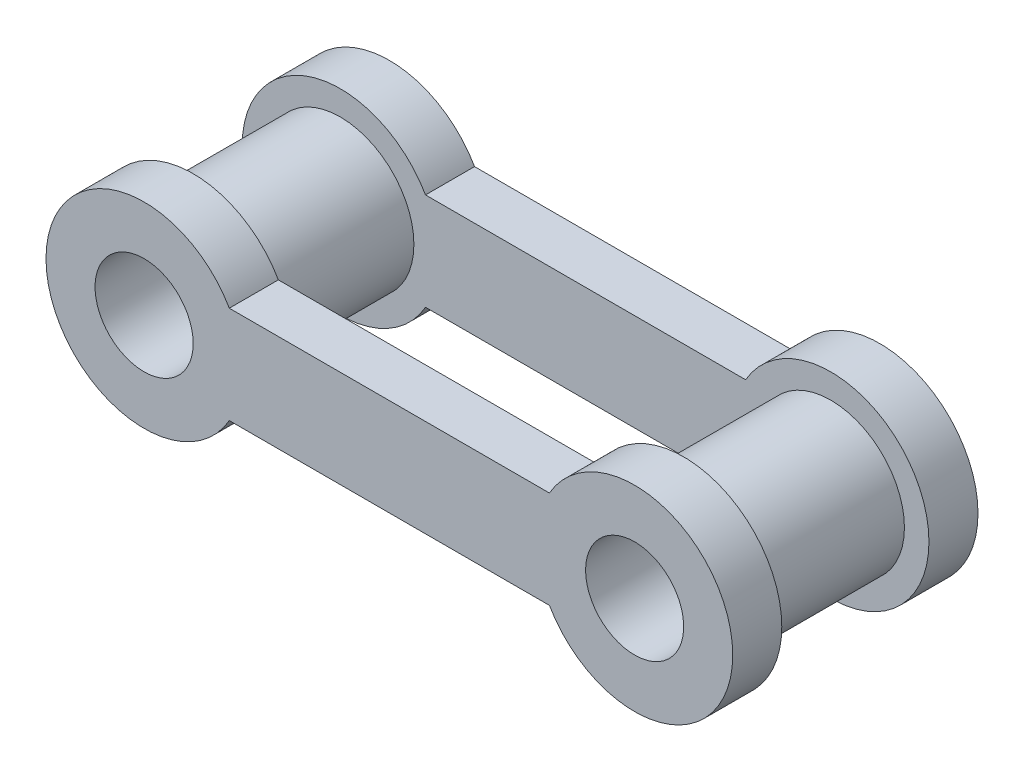
SolidWorks part; units mm, degrees
ref_plane "前视基准面" through (0, 0, 0) normal (0, 0, 1) x (1, 0, 0)
ref_plane "上视基准面" through (0, 0, 0) normal (0, 1, 0) x (1, 0, 0)
ref_plane "右视基准面" through (0, 0, 0) normal (1, 0, 0) x (0, 0, -1)
sketch "草图1" plane through (0, 0, 0) normal (0, 0, 1) x (1, 0, 0)
  line L0 (5.8739, 1.7854) -> (5.8739, 2.6062) construction
  line L1 (5.8739, 2.6062) -> (5.8739, 1.1238) construction
  line L2 (5.8739, 1.7854) -> (-4.2517, 1.7854) construction
  line L3 (-4.2517, 1.7854) -> (-1.6605, 1.7854) construction
  line L4 (-0.6527, 3.7692) -> (12.4005, 3.7692)
  line L5 (-0.6527, -0.1984) -> (12.4005, -0.1984)
  arc A0 (-0.6527, 3.7692) -> (-0.6527, -0.1984) centre (-4.1261, 1.7854) ccw
  circle A1 centre (-4.1261, 1.7854) radius 2
  circle A2 centre (15.8739, 1.7854) radius 2
  arc A3 (12.4005, 3.7692) -> (12.4005, -0.1984) centre (15.8739, 1.7854) cw
  dimension "D2" = 8
  dimension "D3" = 4
  dimension "D1" = 10
extrude "凸台-拉伸1" add sketch "草图1" along normal blind 2
sketch "草图2" plane through (0, 0, 0) normal (0, 0, -1) x (-1, 0, 0)
  line L0 (0, 0) -> (0, 0.7446) construction
  circle A6 centre (4.1261, 1.7854) radius 2 construction
  circle A7 centre (-15.8739, 1.7854) radius 2 construction
  circle A8 centre (4.1261, 1.7854) radius 2
  circle A9 centre (-15.8739, 1.7854) radius 2
  circle A10 centre (-15.8739, 1.7854) radius 3
  circle A11 centre (4.1261, 1.7854) radius 3
extrude "凸台-拉伸2" add sketch "草图2" along normal blind 6
ref_plane "基准面1" through (0, 0, -3) normal (0, 0, -1) x (-1, 0, 0)
mirror "镜向1" about plane through (0, 0, -3) normal (0, 0, -1) of "凸台-拉伸1"
